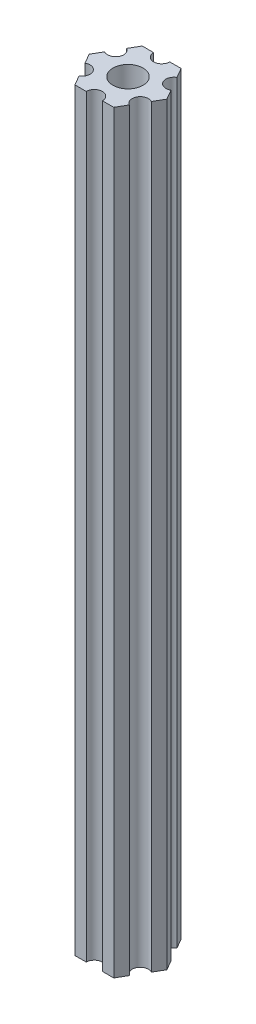
SolidWorks part; units mm, degrees
material "Churro - 6005A-T61"
ref_plane "Plano frontal" through (0, 0, 0) normal (0, 0, 1) x (1, 0, 0)
ref_plane "Plano superior" through (0, 0, 0) normal (0, 1, 0) x (1, 0, 0)
ref_plane "Plano direito" through (0, 0, 0) normal (1, 0, 0) x (0, 0, -1)
ref_plane "Plano1" through (0, 85, 0) normal (0, 1, 0) x (1, 0, 0)
sketch "Esboço1" plane through (0, 85, 0) normal (0, 1, 0) x (1, 0, 0)
  line L0 (6.1627, -1.826) -> (7.2169, 0)
  line L1 (7.2169, 0) -> (6.1627, 1.826)
  line L2 (4.6627, 4.424) -> (3.6084, 6.25)
  line L3 (3.6084, 6.25) -> (1.5, 6.25)
  line L4 (-1.5, 6.25) -> (-3.6084, 6.25)
  line L5 (-3.6084, 6.25) -> (-4.6627, 4.424)
  line L6 (-6.1627, 1.826) -> (-7.2169, 0)
  line L7 (-7.2169, 0) -> (-6.1627, -1.826)
  line L8 (-4.6627, -4.424) -> (-3.6084, -6.25)
  line L9 (-3.6084, -6.25) -> (-1.5, -6.25)
  line L10 (1.5, -6.25) -> (3.6084, -6.25)
  line L11 (3.6084, -6.25) -> (4.6627, -4.424)
  arc A0 (6.1627, 1.826) -> (4.6627, 4.424) centre (5.4127, 3.125) cw
  arc A1 (1.5, 6.25) -> (-1.5, 6.25) centre (0, 6.25) cw
  arc A2 (-4.6627, 4.424) -> (-6.1627, 1.826) centre (-5.4127, 3.125) cw
  arc A3 (-6.1627, -1.826) -> (-4.6627, -4.424) centre (-5.4127, -3.125) cw
  arc A4 (-1.5, -6.25) -> (1.5, -6.25) centre (0, -6.25) cw
  arc A5 (4.6627, -4.424) -> (6.1627, -1.826) centre (5.4127, -3.125) cw
  circle A6 centre (0, 0) radius 2.79
extrude "Ressalto-extrusão1" add sketch "Esboço1" against normal blind 140
